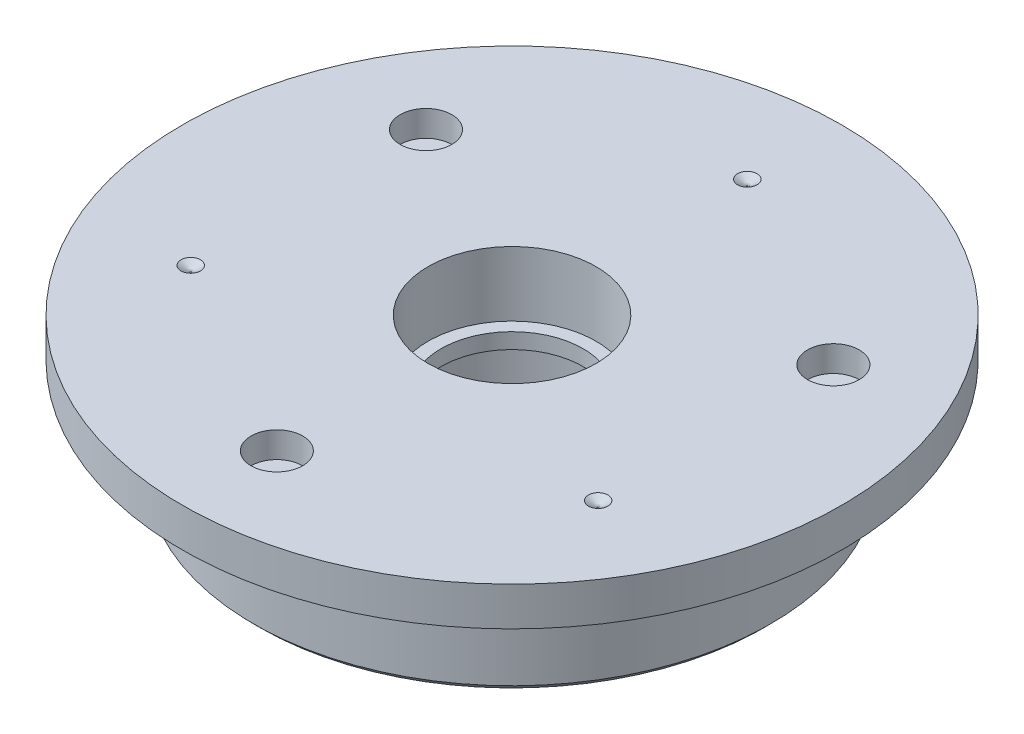
SolidWorks part; units mm, degrees
ref_plane "前视基准面" through (0, 0, 0) normal (0, 0, 1) x (1, 0, 0)
ref_plane "上视基准面" through (0, 0, 0) normal (0, 1, 0) x (1, 0, 0)
ref_plane "右视基准面" through (0, 0, 0) normal (1, 0, 0) x (0, 0, -1)
other "Configuration Table"
sketch "草图1" plane through (0, 0, 0) normal (0, 0, 1) x (1, 0, 0)
  line L0 (25.5, -16.8) -> (0, -16.8)
  line L1 (0, -16.8) -> (0, -19.8)
  line L2 (0, -19.8) -> (25.5, -19.8)
  line L3 (25.5, -19.8) -> (25.5, -16.8)
  line L4 (0, -16.8) -> (0, -19.8) construction
revolve "旋转1" add sketch "草图1" angle 360 about L4
sketch "草图2" plane through (0, -19.8, 0) normal (0, -1, 0) x (1, 0, 0)
  circle A0 centre (0, 0) radius 21.5
extrude "凸台-拉伸1" add sketch "草图2" along normal blind 0.8
sketch "草图3" plane through (0, -20.6, 0) normal (0, -1, 0) x (1, 0, 0)
  circle A0 centre (0, 0) radius 20
extrude "凸台-拉伸2" add sketch "草图3" along normal blind 7.4
ref_plane "基准面1" through (0, 0, 9.1) normal (0, 0, 1) x (1, 0, 0)
sketch "草图4" plane through (0, 0, 9.1) normal (0, 0, 1) x (1, 0, 0)
  line L0 (-15.0109, -16.8) -> (-15.7617, -16.8)
  line L1 (-15.7617, -16.8) -> (-15.7617, -17.2511)
  line L2 (-15.7617, -17.2511) -> (-15.0109, -16.8)
  line L3 (-15.7617, -16.8) -> (-15.7617, -17.2511) construction
revolve "切除-旋转1" cut sketch "草图4" angle 360 about L3
sketch "草图5" plane through (0, 0, 9.1) normal (0, 0, 1) x (1, 0, 0)
  line L0 (16.5124, -16.8) -> (15.7617, -16.8)
  line L1 (15.7617, -16.8) -> (15.7617, -17.2511)
  line L2 (15.7617, -17.2511) -> (16.5124, -16.8)
  line L3 (15.7617, -16.8) -> (15.7617, -17.2511) construction
revolve "切除-旋转2" cut sketch "草图5" angle 360 about L3
ref_plane "基准面2" through (0, 0, -18.2) normal (0, 0, 1) x (1, 0, 0)
sketch "草图6" plane through (0, 0, -18.2) normal (0, 0, 1) x (1, 0, 0)
  line L0 (0.7507, -16.8) -> (0, -16.8)
  line L1 (0, -16.8) -> (0, -17.2511)
  line L2 (0, -17.2511) -> (0.7507, -16.8)
  line L3 (0, -16.8) -> (0, -17.2511) construction
revolve "切除-旋转3" cut sketch "草图6" angle 360 about L3
ref_plane "基准面3" through (0, 0, 0) normal (0, 0, -1) x (-1, 0, 0)
sketch "草图7" plane through (0, 0, 0) normal (0, 0, -1) x (-1, 0, 0)
  line L0 (-9, -28) -> (0, -28)
  line L1 (0, -28) -> (0, -16.8)
  line L2 (0, -16.8) -> (-6.5, -16.8)
  line L3 (-6.5, -16.8) -> (-6.5, -21.8)
  line L4 (-6.5, -21.8) -> (-5.5, -21.8)
  line L5 (-5.5, -21.8) -> (-5.5, -23)
  line L6 (-5.5, -23) -> (-9, -23)
  line L7 (-9, -23) -> (-9, -28)
  line L8 (0, -28) -> (0, -16.8) construction
revolve "切除-旋转4" cut sketch "草图7" angle 360 about L8
hole_wizard "Ø3.0 (3) 直径孔1" positions "草图9" profile "草图8" hole size "Ø3.0" standard "ANSI Metric"
sketch "草图9" plane through (0, -28, 0) normal (0, -1, 0) x (-1, 0, 0)
  point P0 (6, 10.3923)
  point P1 (-6, -10.3923)
sketch "草图8" plane through (-6, -28, -10.3923) normal (1, 0, 0) x (0, 0, -1)
  line L0 (0, 0) -> (0, 3)
  line L1 (0, 3) -> (1.5, 3)
  line L2 (1.5, 3) -> (1.5, 0)
  line L5 (1.5, 0) -> (0, 0)
  line L10 (0, 3) -> (-1.5, 3) construction
  line L11 (0, -6.35) -> (0, 107.95) construction
  dimension "孔直径" = 3
  dimension "孔深度" = 3
  dimension "导头角度" = 180
hole_wizard "Ø3.3 (3.3) 直径孔1" positions "草图11" profile "草图10" hole size "Ø3.3" standard "ANSI Metric"
sketch "草图11" plane through (0, -28, 0) normal (0, -1, 0) x (-1, 0, 0)
  point P0 (10.3923, -6)
  point P1 (0, -12)
  point P2 (-10.3923, -6)
  point P3 (-10.3923, 6)
  point P4 (0, 12)
  point P5 (10.3923, 6)
sketch "草图10" plane through (-10.3923, -28, 6) normal (1, 0, 0) x (0, 0, -1)
  line L0 (0, 0) -> (0, 8.9914)
  line L1 (0, 8.9914) -> (1.65, 8)
  line L2 (1.65, 8) -> (1.65, 0)
  line L5 (1.65, 0) -> (0, 0)
  line L10 (0, 8.9914) -> (-1.65, 8) construction
  line L11 (0, -6.35) -> (0, 107.95) construction
  dimension "孔直径" = 3.3
  dimension "孔深度" = 8
  dimension "导头角度" = 118
hole_wizard "Ø4.0 (4) 直径孔1" positions "草图13" profile "草图12" hole size "Ø4.0" standard "ANSI Metric"
sketch "草图13" plane through (0, -16.8, 0) normal (0, 1, 0) x (1, 0, 0)
  point P0 (15.7617, 9.1)
  point P1 (0, -18.2)
  point P2 (-15.7617, 9.1)
sketch "草图12" plane through (15.7617, -16.8, -9.1) normal (1, 0, 0) x (0, 0, 1)
  line L0 (0, 0) -> (0, 2)
  line L1 (0, 2) -> (2, 2)
  line L2 (2, 2) -> (2, 0)
  line L5 (2, 0) -> (0, 0)
  line L10 (0, 2) -> (-2, 2) construction
  line L11 (0, -6.35) -> (0, 107.95) construction
  dimension "孔直径" = 4
  dimension "孔深度" = 2
  dimension "导头角度" = 180
chamfer "倒角1" distance 0.375 angle 45 6 edges at (0, -28, -13.65) (10.3923, -28, -7.65) (-10.3923, -28, 4.35) (-10.3923, -28, -7.65) (0, -28, 10.35) (10.3923, -28, 4.35)
chamfer "倒角2" distance 0.5 angle 45 1 edges at (0, -28, -20)
